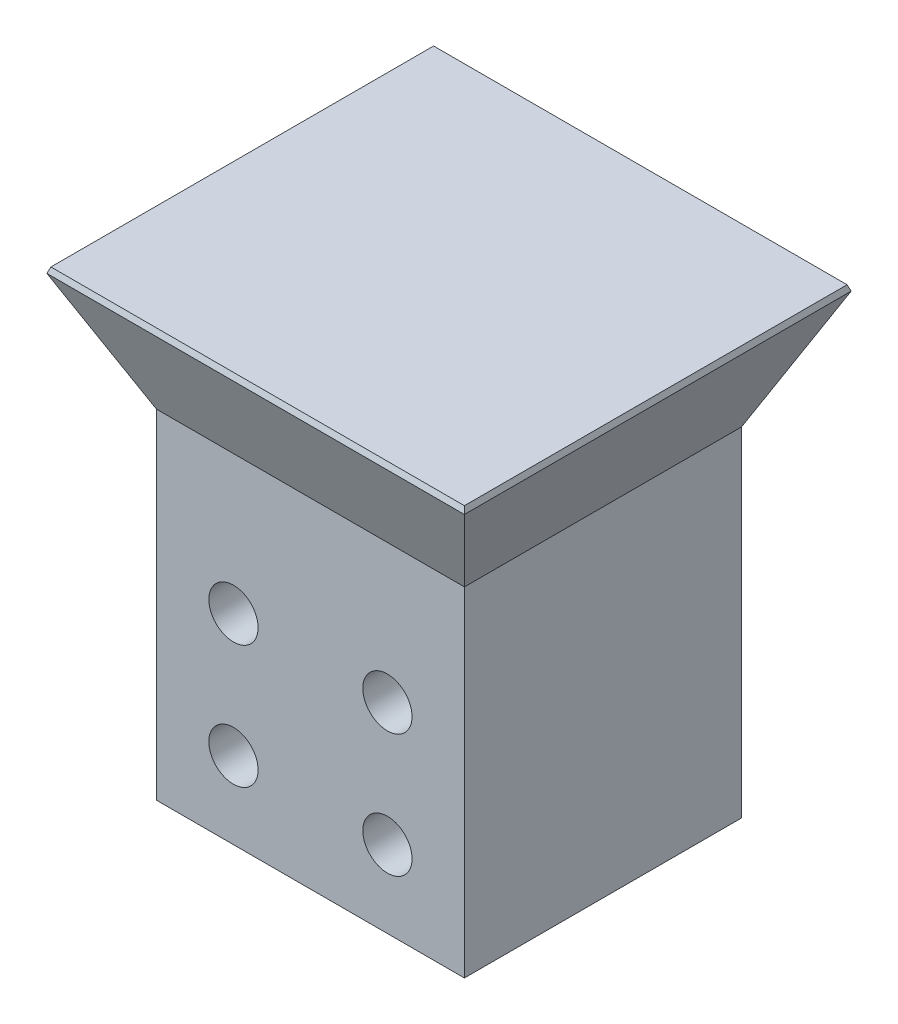
SolidWorks part; units mm, degrees
ref_plane "Front Plane" through (0, 0, 0) normal (0, 0, 1) x (1, 0, 0)
ref_plane "Top Plane" through (0, 0, 0) normal (0, 1, 0) x (1, 0, 0)
ref_plane "Right Plane" through (0, 0, 0) normal (1, 0, 0) x (0, 0, -1)
sketch "Sketch1" plane through (0, 0, 0) normal (0, 1, 0) x (1, 0, 0)
  line L1 (-10, -9) -> (10, -9)
  line L2 (-10, -9) -> (-10, 9)
  line L3 (-10, 9) -> (10, 9)
  line L4 (10, -9) -> (10, 9)
  line L5 (-10, -9) -> (10, 9) construction
  line L6 (-10, 9) -> (10, -9) construction
  point P0 (0, 0)
  dimension "D1" = 18
  dimension "D2" = 20
extrude "Boss-Extrude1" add sketch "Sketch1" along normal blind 22
sketch "Sketch2" plane through (0, 22, 0) normal (0, 1, 0) x (1, 0, 0)
  line L4 (10, -9) -> (10, 9)
  line L5 (10, 9) -> (-10, 9)
  line L6 (-10, 9) -> (-10, -9)
  line L7 (-10, -9) -> (10, -9)
  line L8 (10, -9) -> (10, 9)
  line L9 (10, 9) -> (-10, 9)
  line L10 (-10, 9) -> (-10, -9)
  line L11 (-10, -9) -> (10, -9)
  dimension "D1" = 0
extrude "Boss-Extrude2" add sketch "Sketch2" along normal blind 8 draft 25 draft outward yes
sketch "Sketch3" plane through (0, 0, 9) normal (0, 0, 1) x (1, 0, 0)
  line L0 (-10, 0) -> (10, 0) construction
  line L1 (-10, 22) -> (-10, 0) construction
  circle A0 centre (-5, 13) radius 1.6
  circle A1 centre (5, 13) radius 1.6
  circle A2 centre (-5, 5) radius 1.6
  circle A3 centre (5, 5) radius 1.6
  dimension "D1" = 3.2
  dimension "D2" = 3.2
  dimension "D3" = 3.2
  dimension "D4" = 3.2
  dimension "D5" = 5
  dimension "D6" = 8
  dimension "D7" = 5
  dimension "D8" = 10
extrude "Cut-Extrude1" cut sketch "Sketch3" against normal through all
chamfer "Chamfer1" distance 0.4 angle 45 4 edges at (0, 30, 12.7305) (13.7305, 30, 0) (0, 30, -12.7305) (-13.7305, 30, 0)
